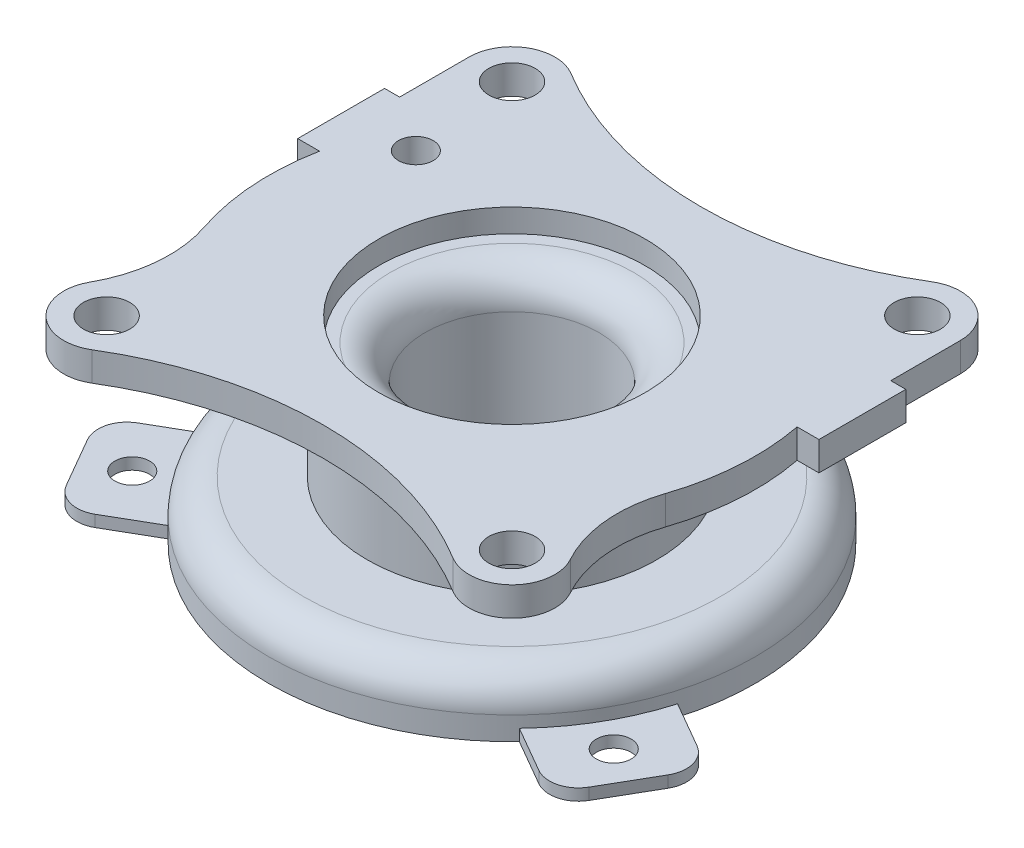
SolidWorks part; units mm, degrees
ref_plane "Front Plane" through (0, 0, 0) normal (0, 0, 1) x (1, 0, 0)
ref_plane "Top Plane" through (0, 0, 0) normal (0, 1, 0) x (1, 0, 0)
ref_plane "Right Plane" through (0, 0, 0) normal (1, 0, 0) x (0, 0, -1)
sketch "Sketch1" plane through (0, 0, 0) normal (0, 0, 1) x (1, 0, 0)
  line L0 (0, 0) -> (0, 10)
  line L1 (0, 10) -> (17, 10)
  line L2 (17, 10) -> (17, 30)
  line L3 (17, 30) -> (12, 30)
  line L4 (12, 30) -> (12, 34)
  line L5 (12, 34) -> (42, 34)
  line L6 (42, 34) -> (42, 0)
  line L7 (42, 0) -> (0, 0)
  dimension "D1" = 42
  dimension "D2" = 30
  dimension "D3" = 10
  dimension "D4" = 4
  dimension "D5" = 25
  dimension "D6" = 30
  dimension "D7" = 34
revolve "Revolve1" add sketch "Sketch1" angle 360 about L6
sketch "Sketch2" plane through (0, 0, 0) normal (0, 1, 0) x (1, 0, 0)
  line L0 (42, 0) -> (42, 62.9253) construction
  line L1 (37, 55) -> (47, 55)
  line L2 (32, 50) -> (32, 40.7922)
  line L4 (52, 50) -> (52, 40.7922)
  circle A0 centre (42, 0) radius 42 construction
  arc A1 (52, 40.7922) -> (32, 40.7922) centre (42, 0) ccw
  circle A2 centre (42, 48) radius 3
  arc A3 (47, 55) -> (52, 50) centre (47, 50) cw
  arc A4 (37, 55) -> (32, 50) centre (37, 50) ccw
  point P12 (52, 55)
  point P15 (32, 55)
  dimension "D4" = 5
  dimension "6" = 6
  dimension "D1" = 20
  dimension "D2" = 55
  dimension "D3" = 48
extrude "Boss-Extrude1" add sketch "Sketch2" along normal blind 2
pattern_circular "CirPattern1" count 3 over 360 about axis through (42, 0, 0) along (0, 1, 0) of "Boss-Extrude1"
hole_wizard "Hole3" positions "Sketch7" profile "Sketch8" legacy end condition up to next
sketch "Sketch7" plane through (0, 34, 0) normal (0, 1, 0) x (1, 0, 0)
  point P0 (42, 0)
sketch "Sketch8" plane through (42, 34, 0) normal (1, 0, 0) x (0, 0, 1)
  line L0 (0, 0) -> (0, 34)
  line L1 (0, 34) -> (15, 34)
  line L2 (15, 34) -> (15, 4)
  line L3 (15, 4) -> (23, 4)
  line L4 (23, 4) -> (23, 0)
  line L5 (23, 0) -> (0, 0)
  line L6 (0, 110) -> (0, -10) construction
  dimension "Diameter" = 30
  dimension "Depth" = 34
  dimension "C-Bore Diameter" = 46
  dimension "C-Bore Depth" = 4
fillet "Fillet1" radius 6 2 edges at (42, 30, 15) (42, 10, 42)
sketch "Sketch9" plane through (0, 34, 0) normal (0, 1, 0) x (1, 0, 0)
  line L0 (42, 0) -> (42, 75.3988) construction
  line L1 (42, 0) -> (138.0065, 0) construction
  line L2 (84.4059, 35) -> (84.4059, 23)
  line L3 (84.4059, 23) -> (87, 23)
  line L4 (87, 23) -> (87, 8)
  line L5 (87, 8) -> (83.2311, 8)
  line L6 (-3, 8) -> (0.7689, 8)
  line L7 (-0.4059, 23) -> (-3, 23)
  line L8 (-3, 23) -> (-3, 8)
  line L9 (-0.4059, 35) -> (-0.4059, 23)
  circle A1 centre (42, 0) radius 30 construction
  circle A2 centre (42, 0) radius 30
  circle A3 centre (77, 35) radius 4
  circle A5 centre (77, -35) radius 4
  arc A6 (0.5228, -31.4092) -> (10.8455, -41.3293) centre (7, -35) ccw
  circle A7 centre (7, -35) radius 4
  circle A9 centre (7, 35) radius 4
  arc A10 (10.8455, 41.3293) -> (73.1545, 41.3293) centre (42, 92.6069) ccw
  arc A11 (10.8455, -41.3293) -> (73.1545, -41.3293) centre (42, -92.6069) cw
  circle A12 centre (42, 0) radius 42 construction
  arc A13 (0.7689, 8) -> (2.1778, -13.3488) centre (42, 0) ccw
  arc A14 (81.8222, -13.3488) -> (83.4772, -31.4092) centre (103.1555, -20.5) ccw
  arc A15 (2.1778, -13.3488) -> (0.5228, -31.4092) centre (-19.1555, -20.5) cw
  arc A16 (10.8455, 41.3293) -> (-0.4059, 35) centre (7, 35) ccw
  arc A21 (84.4059, 35) -> (73.1545, 41.3293) centre (77, 35) ccw
  arc A22 (81.8222, -13.3488) -> (83.2311, 8) centre (42, 0) ccw
  arc A24 (73.1545, -41.3293) -> (83.4772, -31.4092) centre (77, -35) ccw
  point P1 (-24.6737, 37.6422)
  point P4 (-71.0871, 29.9716)
  point P14 (0, 0)
  point P17 (0, 0)
  point P20 (-32.1854, 33.3764)
  point P28 (103.0094, -20.931)
  point P43 (-123.2532, -4.7664)
  dimension "D3" = 20.5
  dimension "D4" = 8
  dimension "D6" = 120
  dimension "D10" = 45
  dimension "D1" = 35
  dimension "D2" = 35
  dimension "D7" = 15
  dimension "D8" = 12
  dimension "D9" = 10
  dimension "D5" = 4
extrude "Boss-Extrude2" add sketch "Sketch9" against normal blind 5
hole_wizard "Hole4" positions "Sketch10" profile "Sketch11" legacy
sketch "Sketch10" plane through (0, 34, 0) normal (0, 1, 0) x (1, 0, 0)
  line L0 (7, 35) -> (7, 5.2469) construction
  point P0 (9, 16.4)
  point P8 (11.0191, 15.7488)
  dimension "D1" = 2
  dimension "D2" = 18.6
sketch "Sketch11" plane through (9, 34, -16.4) normal (1, 0, 0) x (0, 0, 1)
  line L0 (0, 0) -> (0, 5)
  line L1 (0, 5) -> (3, 5)
  line L2 (3, 5) -> (3, 0)
  line L3 (3, 0) -> (0, 0)
  line L4 (0, 110) -> (0, -10) construction
  dimension "Diameter" = 6
  dimension "Depth" = 5
